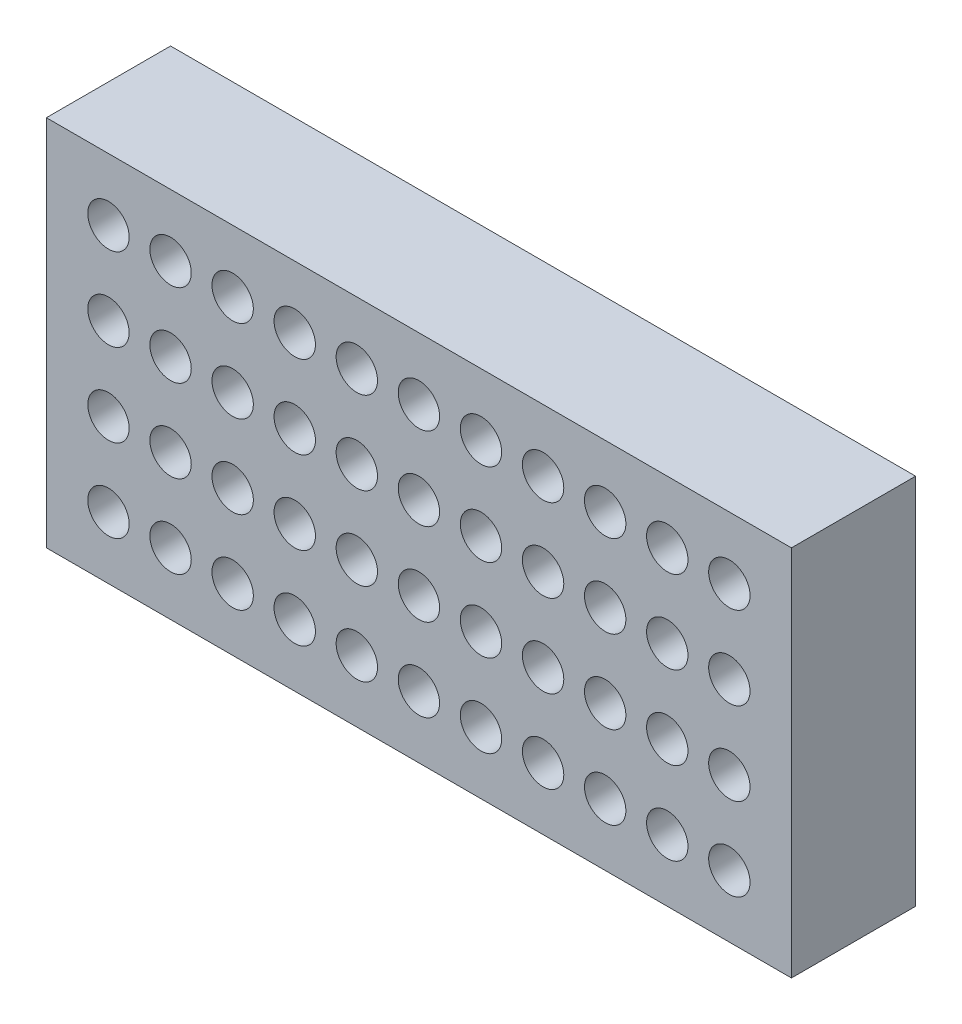
SolidWorks part; units mm, degrees
ref_plane "Plano frontal" through (0, 0, 0) normal (0, 0, 1) x (1, 0, 0)
ref_plane "Plano superior" through (0, 0, 0) normal (0, 1, 0) x (1, 0, 0)
ref_plane "Plano direito" through (0, 0, 0) normal (1, 0, 0) x (0, 0, -1)
sketch "Esboço1" plane through (0, 0, 0) normal (0, 0, 1) x (1, 0, 0)
  line L1 (-90, -45) -> (90, -45)
  line L2 (-90, -45) -> (-90, 45)
  line L3 (-90, 45) -> (90, 45)
  line L4 (90, -45) -> (90, 45)
  line L5 (-90, -45) -> (90, 45) construction
  line L6 (-90, 45) -> (90, -45) construction
  point P0 (0, 0)
  dimension "D1" = 180
  dimension "D2" = 90
extrude "Ressalto-extrusão1" add sketch "Esboço1" along normal blind 30
sketch "Esboço2" plane through (0, 0, 30) normal (0, 0, 1) x (1, 0, 0)
  line L0 (-90, 45) -> (-90, -45) construction
  line L1 (90, 45) -> (-90, 45) construction
  circle A0 centre (-75, 30) radius 5
  circle A1 centre (-60, 30) radius 5
  circle A2 centre (-45, 30) radius 5
  circle A3 centre (-30, 30) radius 5
  circle A4 centre (-15, 30) radius 5
  circle A5 centre (0, 30) radius 5
  circle A6 centre (15, 30) radius 5
  circle A7 centre (30, 30) radius 5
  circle A8 centre (45, 30) radius 5
  circle A9 centre (60, 30) radius 5
  circle A10 centre (75, 30) radius 5
  circle A11 centre (-60, 10) radius 5
  circle A12 centre (-45, 10) radius 5
  circle A13 centre (-30, 10) radius 5
  circle A14 centre (-15, 10) radius 5
  circle A15 centre (0, 10) radius 5
  circle A16 centre (15, 10) radius 5
  circle A17 centre (30, 10) radius 5
  circle A18 centre (45, 10) radius 5
  circle A19 centre (60, 10) radius 5
  circle A20 centre (75, 10) radius 5
  circle A21 centre (-60, -10) radius 5
  circle A22 centre (-45, -10) radius 5
  circle A23 centre (-30, -10) radius 5
  circle A24 centre (-15, -10) radius 5
  circle A25 centre (0, -10) radius 5
  circle A26 centre (15, -10) radius 5
  circle A27 centre (30, -10) radius 5
  circle A28 centre (45, -10) radius 5
  circle A29 centre (60, -10) radius 5
  circle A30 centre (75, -10) radius 5
  circle A31 centre (-60, -30) radius 5
  circle A32 centre (-45, -30) radius 5
  circle A33 centre (-30, -30) radius 5
  circle A34 centre (-15, -30) radius 5
  circle A35 centre (0, -30) radius 5
  circle A36 centre (15, -30) radius 5
  circle A37 centre (30, -30) radius 5
  circle A38 centre (45, -30) radius 5
  circle A39 centre (60, -30) radius 5
  circle A40 centre (75, -30) radius 5
  circle A41 centre (-75, 10) radius 5
  circle A42 centre (-75, -10) radius 5
  circle A43 centre (-75, -30) radius 5
  dimension "D3" = 10
  dimension "D1" = 15
  dimension "D2" = 15
  dimension "D4" = 11
  dimension "D5" = 4
extrude "Corte-extrusão1" cut sketch "Esboço2" against normal blind 30
